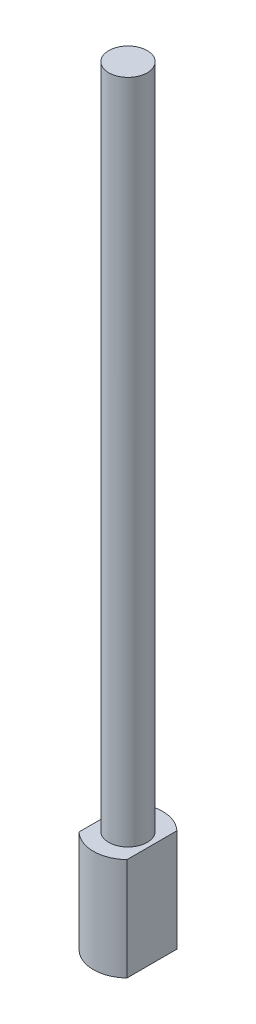
SolidWorks part; units mm, degrees
ref_plane "前视基准面" through (0, 0, 0) normal (0, 0, 1) x (1, 0, 0)
ref_plane "上视基准面" through (0, 0, 0) normal (0, 1, 0) x (1, 0, 0)
ref_plane "右视基准面" through (0, 0, 0) normal (1, 0, 0) x (0, 0, -1)
sketch "草图1" plane through (0, 0, 0) normal (0, 1, 0) x (1, 0, 0)
  circle A0 centre (0, 0) radius 1.5
  dimension "D1" = 3
extrude "凸台-拉伸1" add sketch "草图1" along normal blind 60
sketch "草图2" plane through (0, 0, 0) normal (0, -1, 0) x (1, 0, 0)
  line L0 (0, 0) -> (0, -1.222) construction
  line L2 (-1.87, -1.9476) -> (-1.87, 1.9476)
  line L4 (1.87, -1.9476) -> (1.87, 1.9476)
  arc A0 (-1.87, -1.9476) -> (1.87, -1.9476) centre (0, 0) ccw
  arc A2 (1.87, 1.9476) -> (-1.87, 1.9476) centre (0, 0) ccw
  dimension "D1" = 5.4
  dimension "D2" = 3.74
extrude "凸台-拉伸2" add sketch "草图2" against normal blind 8
